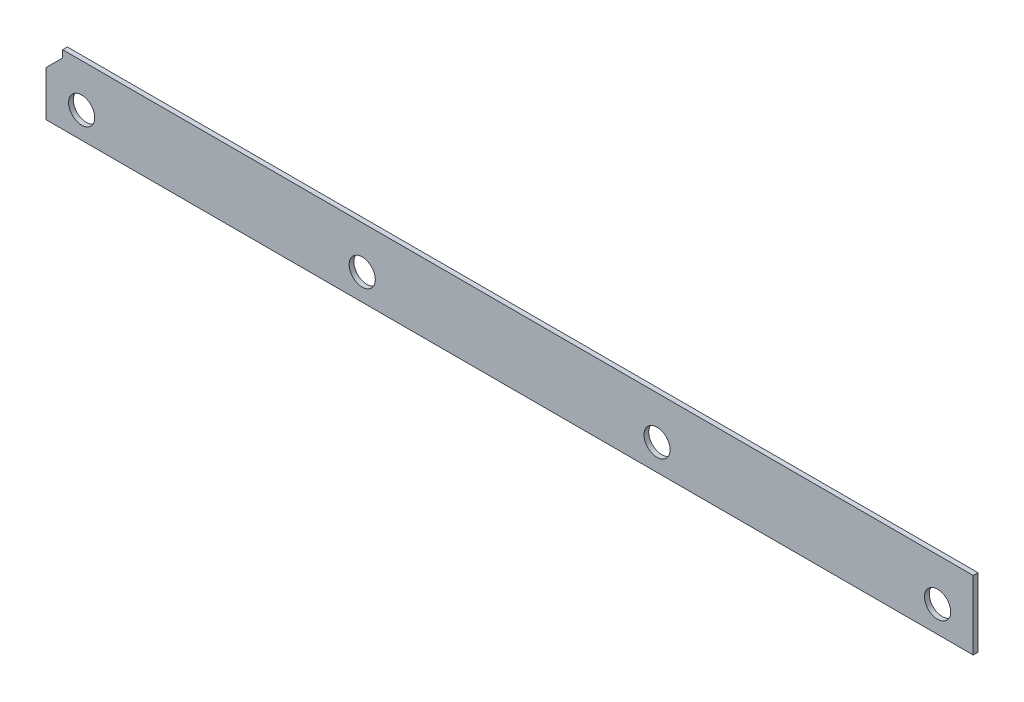
SolidWorks part; units mm, degrees
ref_plane "Front Plane" through (0, 0, 0) normal (0, 0, 1) x (1, 0, 0)
ref_plane "Top Plane" through (0, 0, 0) normal (0, 1, 0) x (1, 0, 0)
ref_plane "Right Plane" through (0, 0, 0) normal (1, 0, 0) x (0, 0, -1)
sketch "Wide flange with original floor bolt centers profile" plane through (0, 0, 0) normal (0, 0, 1) x (1, 0, 0)
  line L0 (97.5, -14.5) -> (-97.5, -14.5)
  line L1 (-97.5, -14.5) -> (-97.5, -5)
  line L2 (-97.5, -5) -> (-94, -1.5)
  line L3 (-94, -1.5) -> (-94, 0)
  line L4 (-94, 0) -> (97.5, 0)
  line L5 (97.5, 0) -> (97.5, -14.5)
  circle A0 centre (90, -9) radius 2.75
  circle A1 centre (31, -9) radius 2.75
  circle A2 centre (-31, -9) radius 2.75
  circle A3 centre (-90, -9) radius 2.75
extrude "Wide flange with original floor bolt centers" add sketch "Wide flange with original floor bolt centers profile" along normal blind 1
